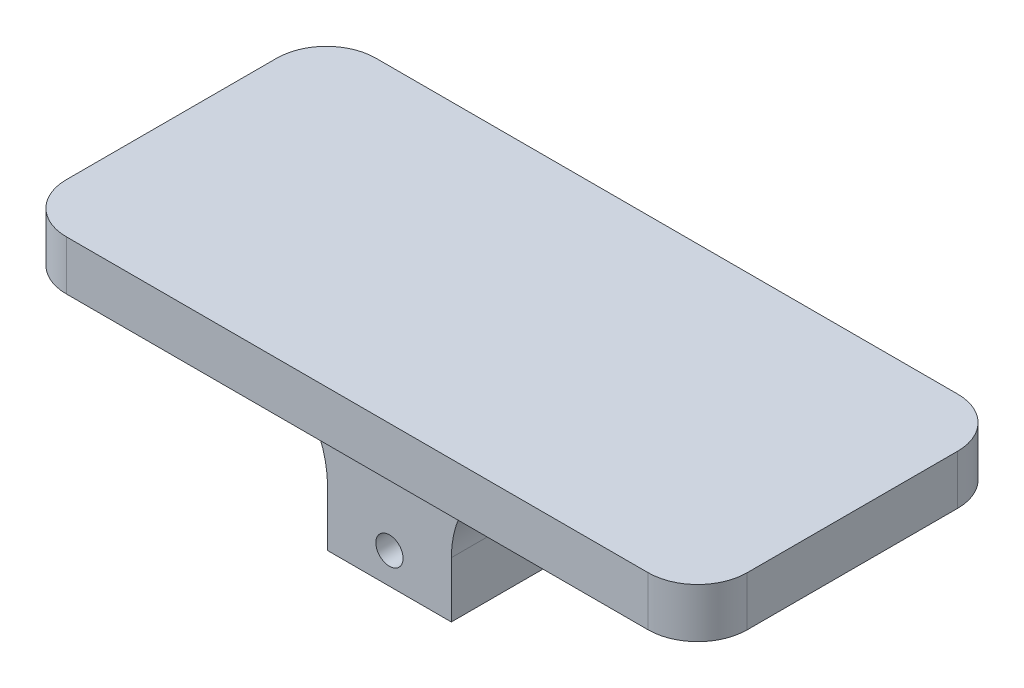
SolidWorks part; units mm, degrees
ref_plane "前视基准面" through (0, 0, 0) normal (0, 0, 1) x (1, 0, 0)
ref_plane "上视基准面" through (0, 0, 0) normal (0, 1, 0) x (1, 0, 0)
ref_plane "右视基准面" through (0, 0, 0) normal (1, 0, 0) x (0, 0, -1)
sketch "草图1" plane through (0, 0, 0) normal (0, 1, 0) x (1, 0, 0)
  line L1 (27.5, -12.5) -> (-27.5, -12.5)
  line L2 (27.5, -12.5) -> (27.5, 12.5)
  line L3 (27.5, 12.5) -> (-27.5, 12.5)
  line L4 (-27.5, -12.5) -> (-27.5, 12.5)
  line L5 (27.5, -12.5) -> (-27.5, 12.5) construction
  line L6 (27.5, 12.5) -> (-27.5, -12.5) construction
  point P0 (0, 0)
  dimension "D1" = 55
  dimension "D2" = 25
extrude "凸台-拉伸1" add sketch "草图1" along normal blind 4
sketch "草图2" plane through (0, 0, 0) normal (0, -1, 0) x (1, 0, 0)
  line L0 (55, 0) -> (-55, 0) construction
  line L1 (-27.5, -12.5) -> (-27.5, 12.5) construction
  circle A0 centre (-22.5, 0) radius 3
  dimension "D1" = 6
  dimension "D2" = 5
extrude "切除-拉伸1" cut sketch "草图2" against normal blind 2.5
sketch "草图3" plane through (0, 2.5, 0) normal (0, -1, 0) x (1, 0, 0)
  circle A0 centre (-22.5, 0) radius 2
  dimension "D1" = 4
extrude "凸台-拉伸2" add sketch "草图3" along normal blind 3.5
sketch "草图5" plane through (0, 0, 0) normal (0, 0, 1) x (1, 0, 0)
  line L0 (-2.5, -1.2697) -> (-2.5, 49998.7303) construction
  line L1 (-27.5, 4) -> (-27.5, 0) construction
  line L2 (-7.5, 0) -> (-7.5, -12.5)
  line L3 (27.5, 0) -> (-27.5, 0) construction
  line L4 (-7.5, -12.5) -> (2.5, -12.5)
  line L5 (2.5, 0) -> (2.5, -12.5)
  line L6 (2.5, 0) -> (-7.5, 0)
  circle A0 centre (-2.5, -10) radius 1.1
  point P11 (-2.5, -12.5)
  dimension "D4" = 2.2
  dimension "D1" = 25
  dimension "D2" = 12.5
  dimension "D3" = 5
  dimension "D5" = 2.5
extrude "凸台-拉伸3" add sketch "草图5" along normal mid plane 14.8
fillet "圆角1" radius 8 2 edges at (2.5, 0, 0) (-7.5, 0, 0)
fillet "圆角2" radius 4 4 edges at (27.5, 2, -12.5) (27.5, 2, 12.5) (-27.5, 2, 12.5) (-27.5, 2, -12.5)
